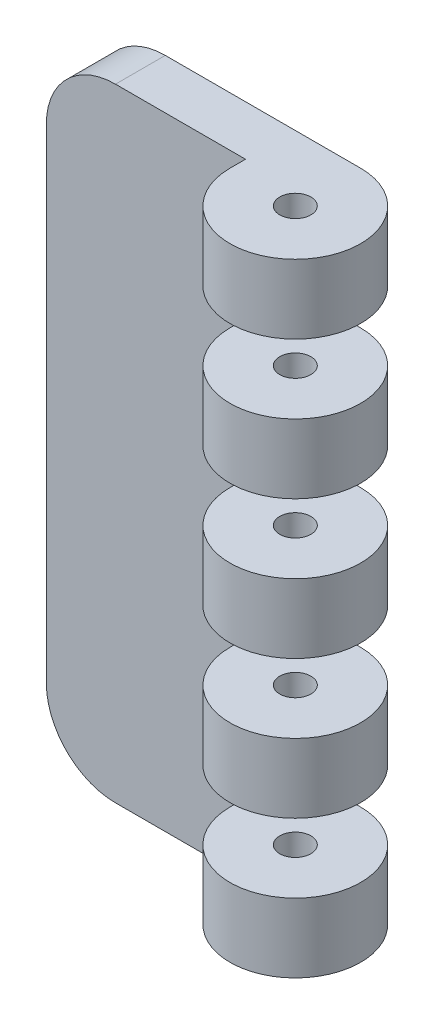
SolidWorks part; units mm, degrees
ref_plane "Front Plane" through (0, 0, 0) normal (0, 0, 1) x (1, 0, 0)
ref_plane "Top Plane" through (0, 0, 0) normal (0, 1, 0) x (1, 0, 0)
ref_plane "Right Plane" through (0, 0, 0) normal (1, 0, 0) x (0, 0, -1)
sketch "Sketch1" plane through (0, 0, 0) normal (0, 0, 1) x (1, 0, 0)
  line L0 (0, -31.75) -> (0, 31.75) construction
  line L1 (1.5875, 31.75) -> (1.5875, -31.75)
  line L2 (-26.9875, 31.75) -> (26.9875, 31.75)
  line L3 (-26.9875, 31.75) -> (-26.9875, -31.75)
  line L4 (-26.9875, -31.75) -> (26.9875, -31.75)
  line L5 (26.9875, 31.75) -> (26.9875, -31.75)
  line L6 (-1.5875, 31.75) -> (-1.5875, -31.75)
  dimension "Frame Leaf Width" = 26.9875
  dimension "Frame Leaf Height" = 63.5
  dimension "Door Leaf Height" = 63.5
  dimension "Door Leaf Width" = 26.9875
  dimension "Overall Width" = 53.975
  dimension "Pin Diameter" = 3.175
sketch "Sketch2" plane through (0, 0, 0) normal (0, 1, 0) x (1, 0, 0)
  line L1 (-26.9875, 6.6675) -> (26.9875, 6.6675)
  line L2 (-26.9875, 6.6675) -> (-26.9875, 1.5875)
  line L3 (-26.9875, 1.5875) -> (26.9875, 1.5875)
  line L4 (26.9875, 6.6675) -> (26.9875, 1.5875)
  circle A0 centre (0, 0) radius 1.5875
  circle A1 centre (0, 0) radius 6.6675
  dimension "D1" = 3.175
  dimension "Leaf Thickness" = 5.08
sketch "Sketch3" plane through (0, 0, 0) normal (0, 1, 0) x (1, 0, 0)
  line L0 (26.9875, 6.6675) -> (26.9875, 1.5875) construction
  line L2 (-26.9875, 6.6675) -> (26.9875, 6.6675) construction
  line L3 (-26.9875, 1.5875) -> (26.9875, 1.5875) construction
  line L4 (26.9875, 6.6675) -> (26.9875, 1.5875)
  line L6 (0, 6.6675) -> (26.9875, 6.6675)
  line L7 (6.6675, 1.5875) -> (26.9875, 1.5875)
  line L8 (6.6675, 0) -> (6.6675, 1.5875)
  circle A0 centre (0, 0) radius 1.5875 construction
  circle A1 centre (0, 0) radius 6.6675 construction
  circle A2 centre (0, 0) radius 1.5875
  arc A3 (0, 6.6675) -> (6.6675, 0) centre (0, 0) ccw
extrude "Boss-Extrude1" add sketch "Sketch3" against normal up to vertex (31.75 mm away) from vertex at 31.75 starting at point (26.9875, 31.75, 0)
fillet "Fillet1" radius 7.0556 2 edges at (26.9875, 31.75, -4.1275) (26.9875, -31.75, -4.1275)
mirror "Mirror1" about plane through (0, 0, 0) normal (1, 0, 0) of bodies 104
sketch "Sketch5" plane through (0, 0, 0) normal (0, 0, 1) x (1, 0, 0)
  line L0 (-26.9875, 31.75) -> (26.9875, 31.75) construction
  line L1 (-8.1915, 31.75) -> (8.1915, 31.75)
  line L2 (-8.1915, 31.75) -> (-8.1915, 24.6944)
  line L3 (-8.1915, 24.6944) -> (8.1915, 24.6944)
  line L4 (8.1915, 31.75) -> (8.1915, 24.6944)
  line L5 (6.6675, -31.75) -> (6.6675, 31.75) construction
  dimension "D1" = 7.0556
  dimension "D2" = 1.524
extrude "Cut-Extrude1" cut sketch "Sketch5" against normal through all both and the other way through all
pattern_linear "LPattern1" count 5 spacing 14.1111 along (0, -1, 0) of "Cut-Extrude1"
fillet "Fillet2" radius 1.1759 8 edges at (8.1915, 24.6944, -4.1275) (8.1915, -24.6944, -4.1275) (8.1915, -17.6389, -4.1275) (8.1915, -10.5833, -4.1275) (8.1915, 3.5278, -4.1275) (8.1915, -3.5278, -4.1275) (8.1915, 10.5833, -4.1275) (8.1915, 17.6389, -4.1275)
sketch "Sketch6" plane through (0, 0, 0) normal (0, 0, 1) x (1, 0, 0)
  line L0 (8.1915, 31.75) -> (8.1915, 24.6944) construction
  line L1 (-8.1915, 24.6944) -> (8.1915, 24.6944)
  line L2 (-8.1915, 24.6944) -> (-8.1915, 17.6389)
  line L3 (-8.1915, 17.6389) -> (8.1915, 17.6389)
  line L4 (8.1915, 24.6944) -> (8.1915, 17.6389)
extrude "Cut-Extrude2" cut sketch "Sketch6" against normal through all both and the other way through all
pattern_linear "LPattern2" count 4 spacing 14.1111 along (0, -1, 0) of "Cut-Extrude2"
fillet "Fillet3" radius 1.1759 8 edges at (-8.1915, -24.6944, -4.1275) (-8.1915, -17.6389, -4.1275) (-8.1915, -10.5833, -4.1275) (-8.1915, -3.5278, -4.1275) (-8.1915, 3.5278, -4.1275) (-8.1915, 10.5833, -4.1275) (-8.1915, 17.6389, -4.1275) (-8.1915, 24.6944, -4.1275)
fillet "Fillet4" radius 0.392 2 edges at (8.1915, -31.75, -4.1275) (8.1915, 31.75, -4.1275)
sketch "Sketch7" plane through (0, 0, 0) normal (0, 1, 0) x (1, 0, 0)
  circle A0 centre (0, 0) radius 1.5875 construction
  circle A1 centre (0, 0) radius 1.5875
extrude "Boss-Extrude3" add sketch "Sketch7" against normal up to vertex (31.75 mm away) from vertex at 31.75 separate body starting at point (-26.9875, 31.75, 0)
delete or keep bodies "Body-Delete/Keep 1" type delete bodies bodies 108
delete or keep bodies "Body-Delete/Keep 2" type delete bodies bodies 112
equation "\"D1@Sketch2\"=\"Pin Diameter@Sketch1\""
equation "\"D1@Fillet1\"=\"Frame Leaf Height@Sketch1\"/9"
equation "\"D1@Sketch5\"=\"Frame Leaf Height@Sketch1\"/9"
equation "\"D3@LPattern1\"=(\"Frame Leaf Height@Sketch1\"/9)*2"
equation "\"D3@LPattern2\"=(\"Frame Leaf Height@Sketch1\"/9)*2"
equation "\"D1@Fillet2\"=(\"Frame Leaf Height@Sketch1\"/9)/6"
equation "\"D1@Fillet3\"=(\"Frame Leaf Height@Sketch1\"/9)/6"
equation "\"D1@Fillet4\"=(\"Frame Leaf Height@Sketch1\"/9)/18"
